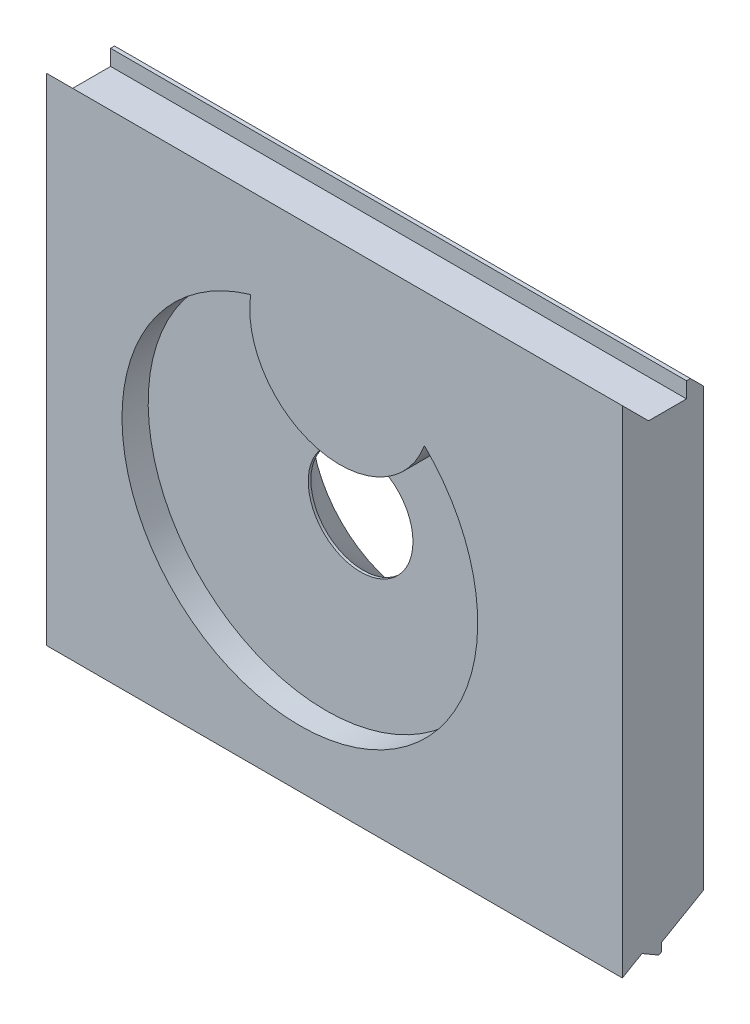
SolidWorks part; units mm, degrees
material "PLA"
ref_plane "Front Plane" through (0, 0, 0) normal (0, 0, 1) x (1, 0, 0)
ref_plane "Top Plane" through (0, 0, 0) normal (0, 1, 0) x (1, 0, 0)
ref_plane "Right Plane" through (0, 0, 0) normal (1, 0, 0) x (0, 0, -1)
sketch "Sketch2" plane through (0, 0, 0) normal (1, 0, 0) x (0, 0, -1)
  line L0 (2, 17.5) -> (4.9, 17.5)
  line L1 (4.9, 17.5) -> (4.9, 18.7)
  line L2 (4.9, 18.7) -> (6.2, 18.7)
  line L3 (6.2, 18.7) -> (6.2, -15.6525)
  line L4 (3, -17.5) -> (0, -17.5) construction
  line L5 (0, -17.5) -> (0, 17.5)
  line L8 (2, 17.5) -> (0, 19.5)
  line L9 (0, 19.5) -> (0, 17.5)
  line L12 (6.2, -15.6525) -> (3, -17.5)
  line L13 (3, -17.5) -> (3, -18.366)
  line L14 (3, -18.366) -> (1.5, -17.5)
  line L15 (1.5, -17.5) -> (0, -18.366)
  line L16 (0, -18.366) -> (0, -17.5)
  point P8 (0, 0)
  dimension "D1" = 35
  dimension "D2" = 6.2
  dimension "D3" = 1.3
  dimension "D4" = 3
  dimension "D5" = 60
  dimension "D6" = 1.2
  dimension "D7" = 37
  dimension "D8" = 45
  dimension "D9" = 30
extrude "Boss-Extrude1" add sketch "Sketch2" along normal mid plane 44 contours L0 L1 L2 L3 L12 L13 L14 L15 L16 L5 L9 L8
sketch "Sketch4" plane through (0, 0, 0) normal (0, 0, 1) x (1, 0, 0)
  circle A0 centre (0, 0.5) radius 4
  dimension "D1" = 8
  dimension "D2" = 0.5
extrude "Cut-Extrude1" cut sketch "Sketch4" against normal through all both and the other way through all
chamfer "Chamfer1" distance 1 angle 45 1 edges at (0, 18.7, -6.2)
chamfer "Chamfer2" distance 4 angle 45 1 edges at (4, 0.5, -6.2)
hole_wizard "CSK for M3 Countersunk Flat Head Screw1" positions "Sketch5" profile "Sketch7" countersink size "M3" standard "ISO"
sketch "Sketch5" plane through (0, 0, -6.2) normal (0, 0, -1) x (-1, 0, 0)
  line L0 (10.5, 0) -> (0, 0)
  line L1 (0, 0) -> (-10.5, 0)
  point P0 (-10.5, 12.5)
  point P2 (10.5, 12.5)
  point P4 (10.5, 0)
  point P6 (-10.5, 0)
  dimension "D1" = 12.5
  dimension "D2" = 21
sketch "Sketch7" plane through (10.5, 12.5, -6.2) normal (1, 0, 0) x (0, 1, 0)
  line L0 (0, 0) -> (0, 3.03)
  line L1 (0, 3.03) -> (0.05, 3)
  line L2 (0.05, 3) -> (0.05, 3.1)
  line L3 (0.05, 3.1) -> (3.15, 0)
  line L5 (3.15, 0) -> (0, 0)
  line L6 (-0.05, 3.1) -> (-3.15, 0) construction
  line L10 (0, 3.03) -> (-0.05, 3) construction
  line L11 (0, -6.35) -> (0, 107.95) construction
  dimension "Hole Dia." = 0.1
  dimension "Hole Depth" = 3
  dimension "Near C'Sink Dia." = 6.3
  dimension "Near C'Sink Angle" = 90
  dimension "Drill Angle" = 118
fillet "Fillet1" radius 0.2 1 edges at (0, -18.366, -3)
sketch "Sketch3" plane through (0, 0, 0) normal (0, 0, 1) x (1, 0, 0)
  arc A0 (6.8755, 9.2942) -> (-6.4032, 12.6518) centre (0.4176, 11.6906) cw
  arc A1 (-6.4032, 12.6518) -> (6.8755, 9.2942) centre (-2.6409, -0.4053) ccw
extrude "Cut-Extrude2" cut sketch "Sketch3" against normal blind 2 contours A1 A0
sketch "Sketch8" [suppressed] plane through (0, 0, 0) normal (0, 0, 1) x (1, 0, 0)
  circle A2 centre (0, -1.0909) radius 12.1052
extrude "Cut-Extrude3" [suppressed] cut sketch "Sketch8" against normal blind 2
sketch "Sketch9" [suppressed] plane through (0, 0, 0) normal (0, 0, 1) x (1, 0, 0)
  line L0 (22, 19.5) -> (22, -18.366) construction
  line L1 (22, 18.7) -> (-22, 18.7) construction
  circle A0 centre (52, 23.247) radius 40
  circle A1 centre (52, 23.247) radius 30
  point P5 (22, 0.567)
  point P8 (0, 18.7)
  dimension "D3" = 10
  dimension "D4" = 80
  dimension "D1" = 22.68
  dimension "D2" = 52
extrude "Boss-Extrude2" [suppressed] add sketch "Sketch9" along normal blind 10 separate body contours A1
sketch "Sketch11" [suppressed] plane through (0, 0, 0) normal (0, 0, 1) x (1, 0, 0)
  line L0 (1.2153, 11.056) -> (0.6979, 1.0694) construction
  arc A0 (-3.7646, 7.7092) -> (5.8226, 7.2125) centre (0.6979, 1.0694) ccw
  arc A1 (5.8226, 7.2125) -> (-3.7646, 7.7092) centre (1.2153, 11.056) cw
  dimension "D1" = 8
  dimension "D3" = 6
  dimension "10" = 10
extrude "Cut-Extrude4" [suppressed] cut sketch "Sketch11" against normal blind 2
sketch "Sketch10" [suppressed] plane through (0, 0, 0) normal (0, 0, 1) x (1, 0, 0)
  line L1 (0, 17.2828) -> (-21.8863, 41.693) construction
  line L2 (-21.8863, 41.693) -> (-22, -11.056) construction
  line L5 (-22, -11.056) -> (-15.1084, -21.4889) construction
  line L7 (-15.1084, -21.4889) -> (-87.0427, -28.8331) construction
  line L8 (-87.0427, -28.8331) -> (-59.4928, 9.0286) construction
  line L9 (-59.4928, 9.0286) -> (-49.3626, 12.5695) construction
  line L10 (-49.3626, 12.5695) -> (-39.2122, 5.69) construction
  line L11 (-39.2122, 5.69) -> (-39.2122, -2.1276) construction
  line L13 (0, 17.2828) -> (0, 10.4013)
  line L16 (0, 10.4013) -> (-15.2284, 7.6006) construction
  line L20 (-15.2284, 7.6006) -> (-22, -8.6692) construction
  line L21 (-22, -8.6692) -> (-37.09, -26.9512) construction
  line L22 (-37.09, -26.9512) -> (-52.4849, -25.4876) construction
  line L23 (-52.4849, -25.4876) -> (-79.8114, -12.2652) construction
  line L24 (-79.8114, -12.2652) -> (-64.6057, 11.3468) construction
  line L25 (-64.6057, 11.3468) -> (-51.244, 18.7138) construction
  line L26 (-51.244, 18.7138) -> (-38.6703, 7.8759) construction
  line L27 (-38.6703, 7.8759) -> (-36.3992, 5.4848) construction
  line L28 (-36.3992, 5.4848) -> (-39.2122, -2.1276) construction
  line L29 (-22, -18.366) -> (-22, 19.5) construction
extrude "Boss-Extrude3" [suppressed] add sketch "Sketch10" along normal blind 3 separate body
mirror "Mirror1" [suppressed]
